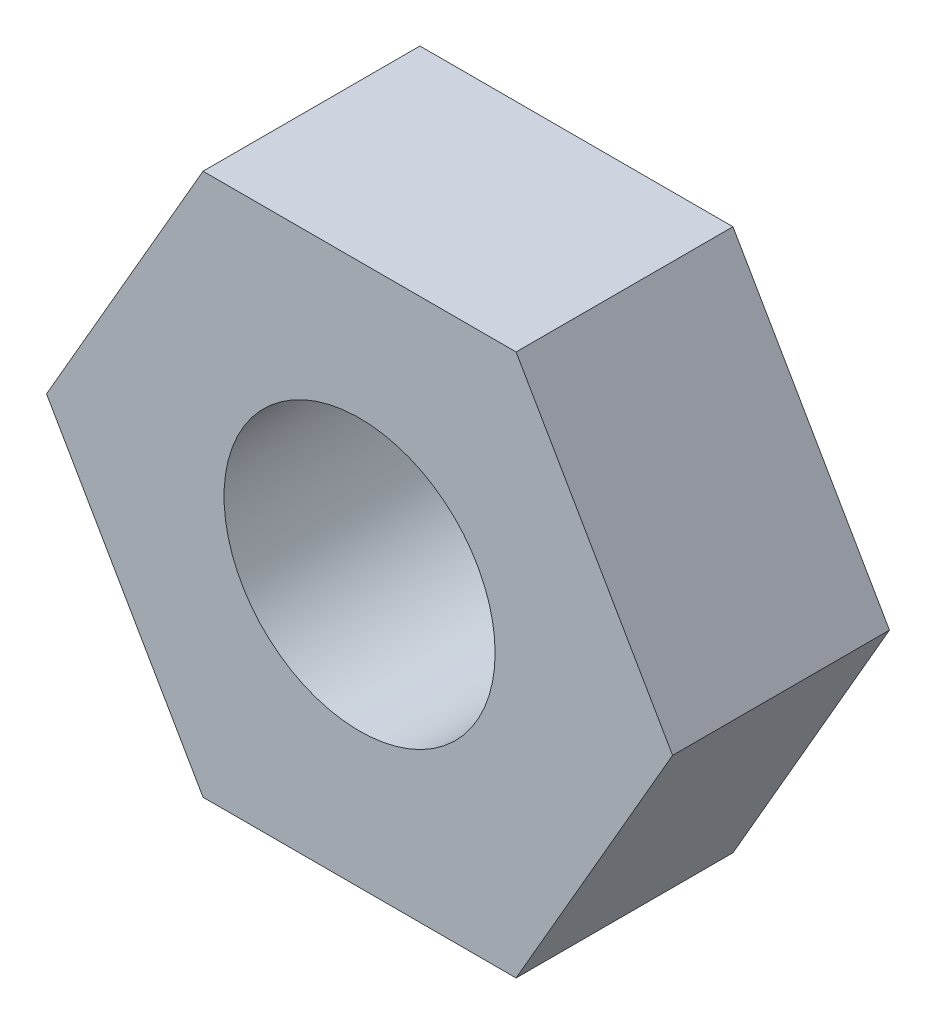
SolidWorks part; units mm, degrees
ref_plane "Plan de face" through (0, 0, 0) normal (0, 0, 1) x (1, 0, 0)
ref_plane "Plan de dessus" through (0, 0, 0) normal (0, 1, 0) x (1, 0, 0)
ref_plane "Plan de droite" through (0, 0, 0) normal (1, 0, 0) x (0, 0, -1)
sketch "Esquisse1" plane through (0, 0, 0) normal (0, 0, 1) x (1, 0, 0)
  line L1 (2.3094, 0) -> (1.1547, 2)
  line L2 (1.1547, 2) -> (-1.1547, 2)
  line L3 (-1.1547, 2) -> (-2.3094, 0)
  line L4 (-2.3094, 0) -> (-1.1547, -2)
  line L5 (-1.1547, -2) -> (1.1547, -2)
  line L6 (1.1547, -2) -> (2.3094, 0)
  circle A0 centre (0, 0) radius 1
  circle A1 centre (0, 0) radius 2 construction
  dimension "D1" = 2
  dimension "D2" = 4
extrude "Boss.-Extru.1" add sketch "Esquisse1" along normal blind 1.6
